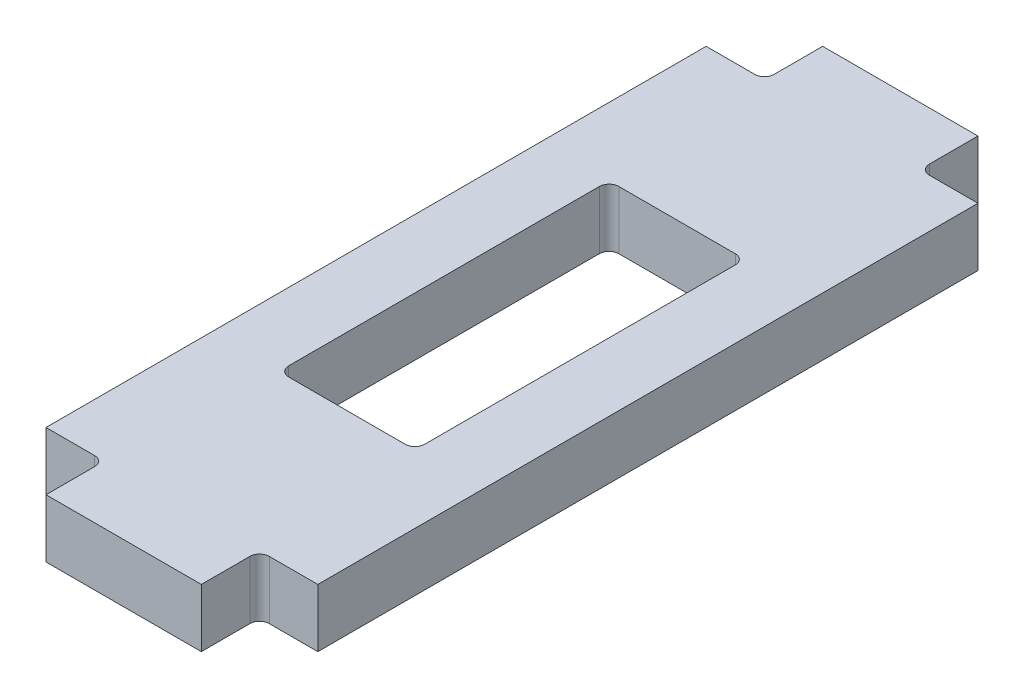
SolidWorks part; units mm, degrees
material "Thornel Mat VMA"
ref_plane "前视基准面" through (0, 0, 0) normal (0, 0, 1) x (1, 0, 0)
ref_plane "上视基准面" through (0, 0, 0) normal (0, 1, 0) x (1, 0, 0)
ref_plane "右视基准面" through (0, 0, 0) normal (1, 0, 0) x (0, 0, -1)
sketch "草图1" plane through (0, 0, 0) normal (0, 1, 0) x (1, 0, 0)
  line L1 (-7, 17) -> (7, 17)
  line L2 (-7, 17) -> (-7, -17)
  line L3 (-7, -17) -> (7, -17)
  line L4 (7, 17) -> (7, -17)
  line L5 (-7, 17) -> (7, -17) construction
  line L6 (-7, -17) -> (7, 17) construction
  line L7 (-4, 20) -> (4, 20)
  line L8 (-4, 20) -> (-4, 14)
  line L9 (-4, 14) -> (4, 14)
  line L10 (4, 20) -> (4, 14)
  line L11 (-4, 20) -> (4, 14) construction
  line L12 (-4, 14) -> (4, 20) construction
  line L13 (-4, -14) -> (4, -14)
  line L14 (-4, -14) -> (-4, -20)
  line L15 (-4, -20) -> (4, -20)
  line L16 (4, -14) -> (4, -20)
  line L17 (-4, -14) -> (4, -20) construction
  line L18 (-4, -20) -> (4, -14) construction
  line L19 (-3.5, 8.5) -> (3.5, 8.5)
  line L20 (-3.5, 8.5) -> (-3.5, -8.5)
  line L21 (-3.5, -8.5) -> (3.5, -8.5)
  line L22 (3.5, 8.5) -> (3.5, -8.5)
  line L23 (-3.5, 8.5) -> (3.5, -8.5) construction
  line L24 (-3.5, -8.5) -> (3.5, 8.5) construction
  point P0 (0, 0)
  point P5 (0, 17)
  point P11 (0, -17)
  point P16 (0, 0)
  dimension "D1" = 34
  dimension "D2" = 14
  dimension "D3" = 6
  dimension "D4" = 8
  dimension "D5" = 6
  dimension "D6" = 8
  dimension "D7" = 17
  dimension "D8" = 7
extrude "凸台-拉伸1" add sketch "草图1" along normal blind 3 contours L13 L16 L3 L4 L1 L10 L9 L8 L2 L14 L19 L22 L21 L20 | L10 L7 L8 L1 | L10 L1 L8 L9 | L16 L3 L14 L15 | L16 L13 L14 L3
fillet "圆角1" radius 0.5 8 edges at (-3.5, 1.5, 8.5) (3.5, 1.5, 8.5) (3.5, 1.5, -8.5) (-3.5, 1.5, -8.5) (4, 1.5, 17) (-4, 1.5, 17) (4, 1.5, -17) (-4, 1.5, -17)
